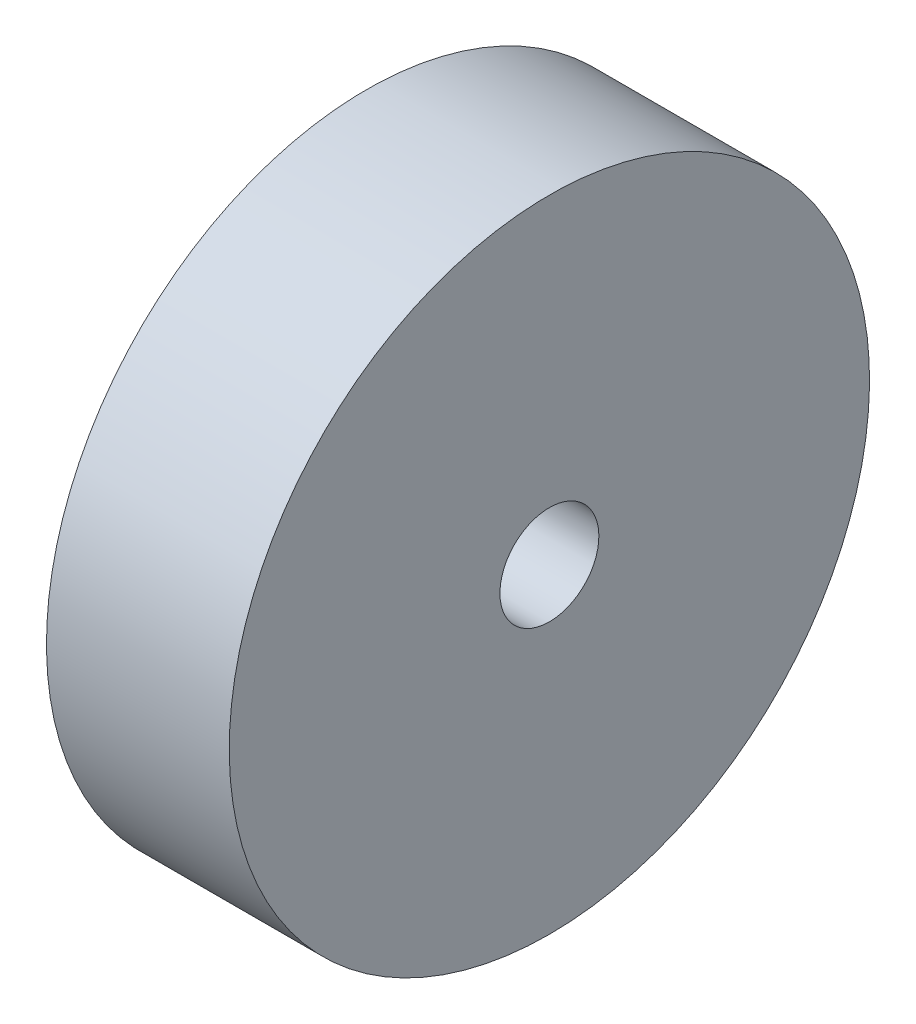
SolidWorks part; units mm, degrees
ref_plane "Front Plane" through (0, 0, 0) normal (0, 0, 1) x (1, 0, 0)
ref_plane "Top Plane" through (0, 0, 0) normal (0, 1, 0) x (1, 0, 0)
ref_plane "Right Plane" through (0, 0, 0) normal (1, 0, 0) x (0, 0, -1)
sketch "Sketch1" plane through (0, 0, 0) normal (0, 0, 1) x (1, 0, 0)
  line L0 (-0.785, 0.425) -> (0.785, 0.425)
  line L1 (-0.785, 2.75) -> (0.785, 2.75)
  line L2 (-0.785, 2.75) -> (-0.785, 0.425)
  line L3 (-0.785, 0) -> (0.785, 0) construction
  line L4 (0.785, 2.75) -> (0.785, 0.425)
  dimension "D1" = 2.75
  dimension "D2" = 1.57
  dimension "D3" = 0.425
revolve "Revolve1" add sketch "Sketch1" angle 360 about L3
